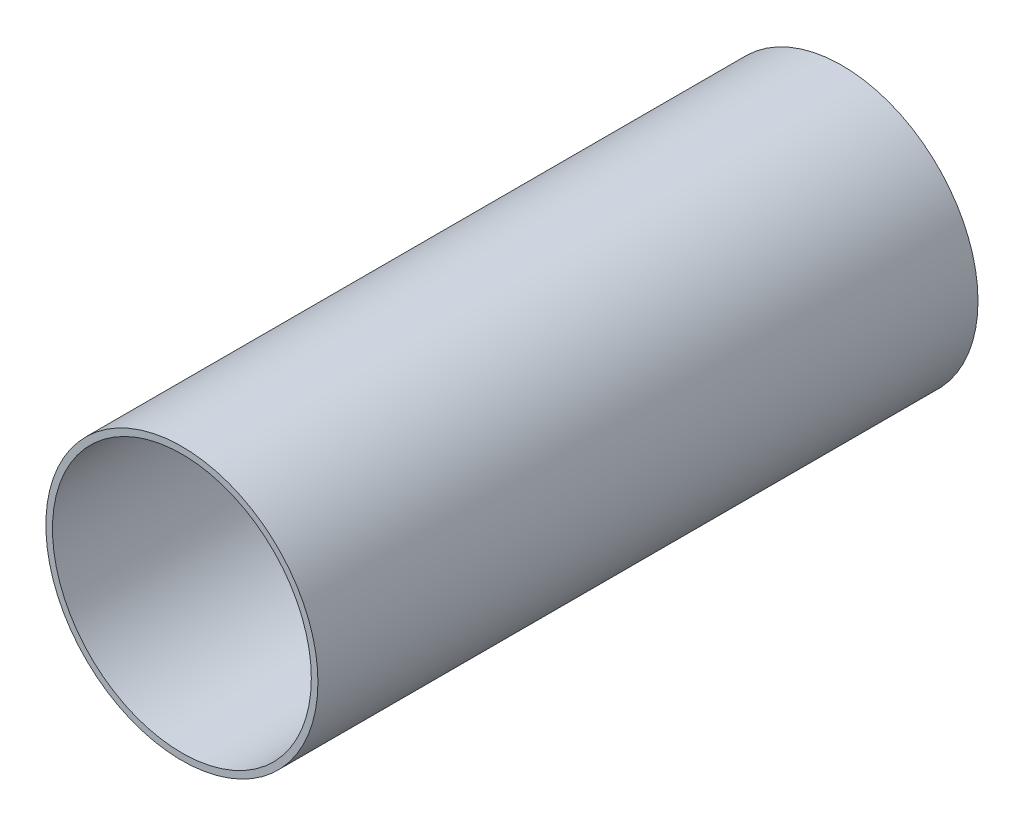
SolidWorks part; units mm, degrees
ref_plane "Front Plane" through (0, 0, 0) normal (0, 0, 1) x (1, 0, 0)
ref_plane "Top Plane" through (0, 0, 0) normal (0, 1, 0) x (1, 0, 0)
ref_plane "Right Plane" through (0, 0, 0) normal (1, 0, 0) x (0, 0, -1)
sketch "Sketch18" plane through (0, 0, 0) normal (0, 0, 1) x (1, 0, 0)
  circle A0 centre (0, 0) radius 16.9
  dimension "D1" = 33.8
extrude "Boss-Extrude6" add sketch "Sketch18" along normal blind 82
sketch "Sketch19" plane through (0, 0, 82) normal (0, 0, 1) x (1, 0, 0)
  circle A0 centre (0, 0) radius 16.08
  dimension "D1" = 32.16
extrude "Cut-Extrude2" cut sketch "Sketch19" against normal through all
